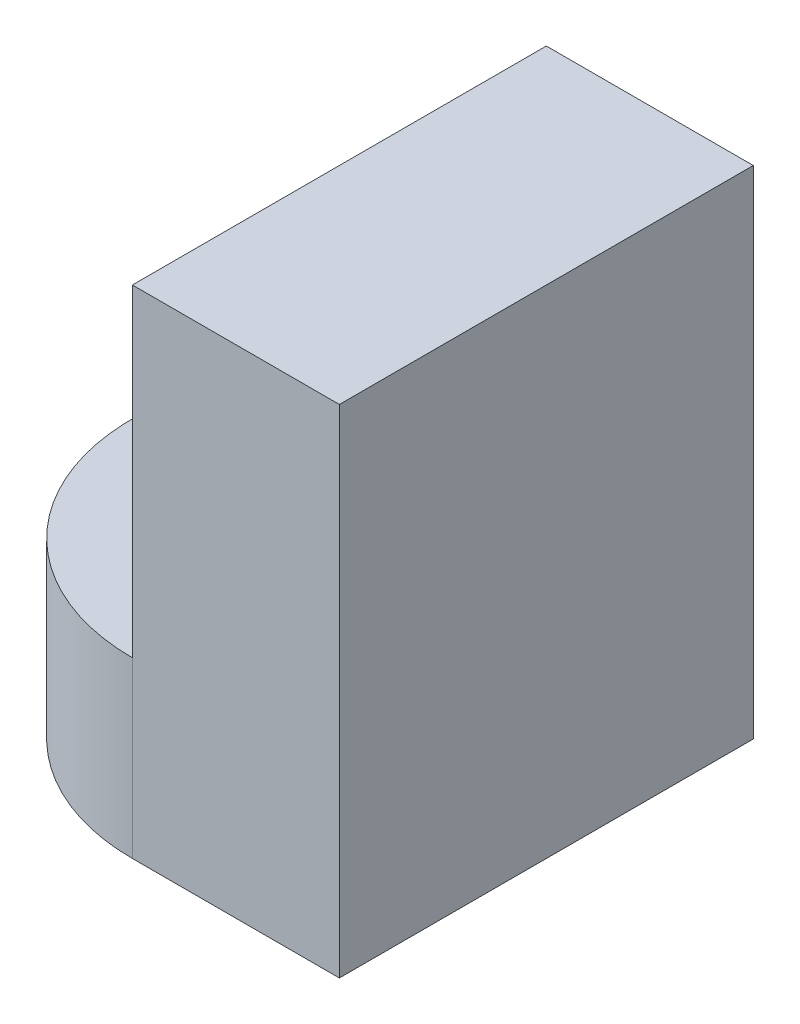
SolidWorks part; units mm, degrees
ref_plane "Front Plane" through (0, 0, 0) normal (0, 0, 1) x (1, 0, 0)
ref_plane "Top Plane" through (0, 0, 0) normal (0, 1, 0) x (1, 0, 0)
ref_plane "Right Plane" through (0, 0, 0) normal (1, 0, 0) x (0, 0, -1)
sketch "Sketch1" plane through (0, 0, 0) normal (0, 1, 0) x (1, 0, 0)
  circle A1 centre (0, 0) radius 2.5
  dimension "D2" = 5
extrude "Boss-Extrude2" add sketch "Sketch1" along normal blind 2.1
ref_plane "Plane1" through (2.5, 0, 0) normal (1, 0, 0) x (0, 0, -1)
sketch "Sketch10" plane through (2.5, 0, 0) normal (1, 0, 0) x (0, 0, -1)
  line L0 (-2.5, 0) -> (-2.5, 6)
  line L1 (-2.5, 0) -> (2.5, 0)
  line L2 (2.5, 0) -> (2.5, 6)
  line L3 (2.5, 6) -> (-2.5, 6)
  dimension "D1" = 6
  dimension "D2" = 5
extrude "Boss-Extrude5" add sketch "Sketch10" against normal blind 2.5
sketch "Sketch11" plane through (0, 0, 0) normal (-1, 0, 0) x (0, 0, 1)
  line L0 (-1.387, 4) -> (1.613, 4)
  arc A0 (1.613, 4) -> (-1.387, 4) centre (0.113, 4) ccw
  dimension "D1" = 1.5
  dimension "D2" = 4
revolve "Cut-Revolve2" cut sketch "Sketch11" angle 360 about L0
sketch "Sketch12" plane through (0, 0, 0) normal (0, -1, 0) x (1, 0, 0)
  circle A0 centre (0, 0) radius 1
  dimension "D1" = 2
extrude "Cut-Extrude1" cut sketch "Sketch12" against normal blind 2
